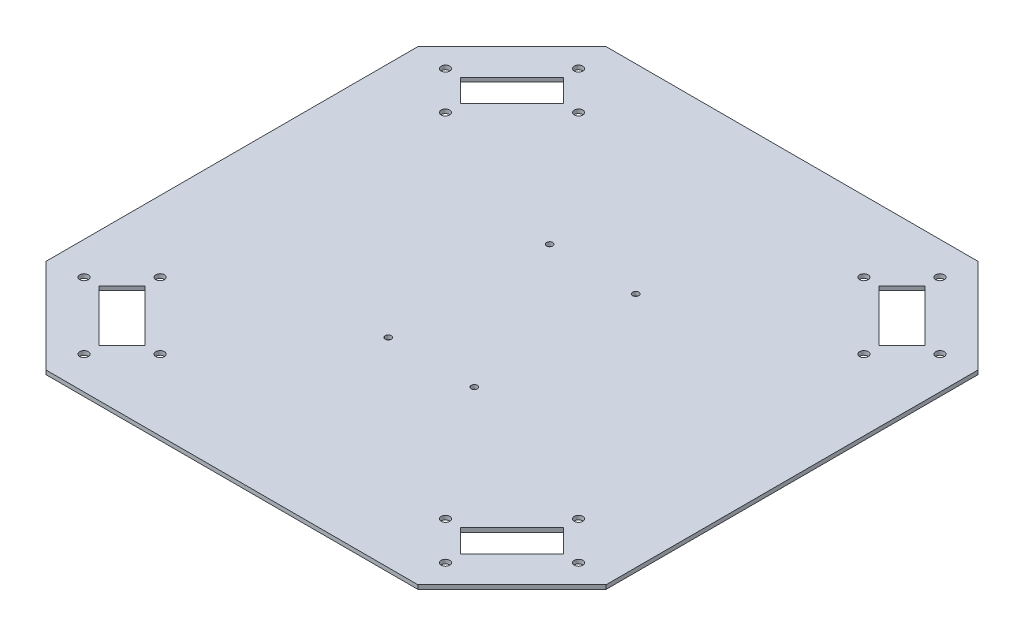
SolidWorks part; units mm, degrees
material "Carbon fiber"
ref_plane "Front Plane" through (0, 0, 0) normal (0, 0, 1) x (1, 0, 0)
ref_plane "Top Plane" through (0, 0, 0) normal (0, 1, 0) x (1, 0, 0)
ref_plane "Right Plane" through (0, 0, 0) normal (1, 0, 0) x (0, 0, -1)
sketch "Sketch2" plane through (0, 0, 0) normal (0, 1, 0) x (1, 0, 0)
  line L0 (91.9419, 67.1932) -> (67.1932, 91.9419) construction
  line L5 (67.1932, 91.9419) -> (53.051, 77.7998) construction
  line L6 (53.051, 77.7998) -> (77.7998, 53.051) construction
  line L7 (77.7998, 53.051) -> (91.9419, 67.1932) construction
  line L8 (-67.1932, 91.9419) -> (-91.9419, 67.1932) construction
  line L9 (-91.9419, 67.1932) -> (-77.7998, 53.051) construction
  line L10 (-77.7998, 53.051) -> (-53.051, 77.7998) construction
  line L11 (-53.051, 77.7998) -> (-67.1932, 91.9419) construction
  line L12 (-67.1932, -91.9419) -> (-91.9419, -67.1932) construction
  line L13 (-91.9419, -67.1932) -> (-77.7998, -53.051) construction
  line L14 (-77.7998, -53.051) -> (-53.051, -77.7998) construction
  line L15 (-53.051, -77.7998) -> (-67.1932, -91.9419) construction
  line L16 (67.1932, -91.9419) -> (91.9419, -67.1932) construction
  line L17 (91.9419, -67.1932) -> (77.7998, -53.051) construction
  line L18 (77.7998, -53.051) -> (53.051, -77.7998) construction
  line L19 (53.051, -77.7998) -> (67.1932, -91.9419) construction
  line L20 (86.6386, 86.6386) -> (79.5675, 79.5675) construction
  line L21 (79.5675, 79.5675) -> (76.7391, 76.7391) construction
  line L22 (-76.7391, -76.7391) -> (-79.5675, -79.5675) construction
  line L23 (-79.5675, -79.5675) -> (-86.6386, -86.6386) construction
  line L24 (-86.6386, 86.6386) -> (-79.5675, 79.5675) construction
  line L25 (-79.5675, 79.5675) -> (-76.7391, 76.7391) construction
  line L26 (104.1386, -69.1386) -> (104.1386, 69.1386)
  line L27 (69.1386, 104.1386) -> (-69.1386, 104.1386)
  line L28 (-104.1386, 69.1386) -> (-104.1386, -69.1386)
  line L29 (-69.1386, -104.1386) -> (69.1386, -104.1386)
  line L30 (86.6386, -86.6386) -> (79.5675, -79.5675) construction
  line L31 (79.5675, -79.5675) -> (76.7391, -76.7391) construction
  line L33 (104.1386, 69.1386) -> (69.1386, 104.1386)
  line L34 (69.1386, -104.1386) -> (104.1386, -69.1386)
  line L35 (-104.1386, -69.1386) -> (-69.1386, -104.1386)
  line L36 (0, 104.1386) -> (0, 0) construction
  line L37 (0, 0) -> (104.1386, 0) construction
  line L38 (86.2851, -67.1932) -> (77.7998, -58.7079)
  line L39 (67.1932, -86.2851) -> (86.2851, -67.1932)
  line L40 (77.7998, -58.7079) -> (58.7079, -77.7998)
  line L41 (58.7079, -77.7998) -> (67.1932, -86.2851)
  line L42 (-67.1932, -86.2851) -> (-58.7079, -77.7998)
  line L43 (-86.2851, -67.1932) -> (-67.1932, -86.2851)
  line L44 (-77.7998, -58.7079) -> (-86.2851, -67.1932)
  line L45 (-58.7079, -77.7998) -> (-77.7998, -58.7079)
  line L46 (-86.2851, 67.1932) -> (-77.7998, 58.7079)
  line L47 (-67.1932, 86.2851) -> (-86.2851, 67.1932)
  line L48 (-58.7079, 77.7998) -> (-67.1932, 86.2851)
  line L49 (-77.7998, 58.7079) -> (-58.7079, 77.7998)
  line L50 (77.7998, 58.7079) -> (86.2851, 67.1932)
  line L51 (86.2851, 67.1932) -> (67.1932, 86.2851)
  line L52 (67.1932, 86.2851) -> (58.7079, 77.7998)
  line L53 (58.7079, 77.7998) -> (77.7998, 58.7079)
  line L54 (-69.1386, 104.1386) -> (-104.1386, 104.1386) construction
  line L55 (-104.1386, 104.1386) -> (-104.1386, 69.1386) construction
  line L56 (-104.1386, -69.1386) -> (-104.1386, -104.1386) construction
  line L57 (-104.1386, -104.1386) -> (-69.1386, -104.1386) construction
  line L58 (69.1386, -104.1386) -> (104.1386, -104.1386) construction
  line L59 (104.1386, -104.1386) -> (104.1386, -69.1386) construction
  line L60 (104.1386, 69.1386) -> (104.1386, 104.1386) construction
  line L61 (104.1386, 104.1386) -> (69.1386, 104.1386) construction
  line L62 (-69.1386, 104.1386) -> (-104.1386, 69.1386)
  line L63 (-16, 0) -> (0, 0) construction
  line L64 (-16, 30) -> (16, 30) construction
  line L65 (-16, 30) -> (-16, -30) construction
  line L66 (-16, -30) -> (16, -30) construction
  line L67 (16, 30) -> (16, -30) construction
  line L68 (0, 0) -> (0, -30) construction
  circle A0 centre (67.1932, -91.9419) radius 1.6
  circle A1 centre (53.051, -77.7998) radius 1.6
  circle A2 centre (77.7998, -53.051) radius 1.6
  circle A3 centre (91.9419, -67.1932) radius 1.6
  circle A4 centre (-67.1932, -91.9419) radius 1.6
  circle A5 centre (-91.9419, -67.1932) radius 1.6
  circle A6 centre (-77.7998, -53.051) radius 1.6
  circle A7 centre (-53.051, -77.7998) radius 1.6
  circle A8 centre (-77.7998, 53.051) radius 1.6
  circle A9 centre (-53.051, 77.7998) radius 1.6
  circle A10 centre (-67.1932, 91.9419) radius 1.6
  circle A11 centre (-91.9419, 67.1932) radius 1.6
  circle A12 centre (77.7998, 53.051) radius 1.6
  circle A13 centre (53.051, 77.7998) radius 1.6
  circle A14 centre (67.1932, 91.9419) radius 1.6
  circle A15 centre (91.9419, 67.1932) radius 1.6
  circle A17 centre (0, 0) radius 125 construction
  circle A18 centre (16, 30) radius 1.15
  circle A19 centre (-16, 30) radius 1.15
  circle A20 centre (-16, -30) radius 1.15
  circle A21 centre (16, -30) radius 1.15
  point P2 (104.1386, -104.1386)
  point P6 (104.1386, 104.1386)
  point P12 (-104.1386, 104.1386)
  point P23 (-104.1386, -104.1386)
  dimension "D1" = 3.2
  dimension "D5" = 3.2
  dimension "D11" = 3.2
  dimension "D16" = 3.2
  dimension "D26" = 250
  dimension "D41" = 2.3
  dimension "D3" = 20
  dimension "D4" = 4
  dimension "D6" = 4
  dimension "D7" = 4
  dimension "D8" = 20
  dimension "D9" = 10
  dimension "D10" = 35
  dimension "D12" = 35
  dimension "D13" = 20
  dimension "D14" = 4
  dimension "D15" = 4
  dimension "D18" = 20
  dimension "D19" = 4
  dimension "D20" = 4
  dimension "D21" = 4
  dimension "D22" = 4
  dimension "D23" = 4
  dimension "D24" = 4
  dimension "D29" = 35
  dimension "D32" = 35
  dimension "D33" = 35
  dimension "D34" = 35
  dimension "D35" = 35
  dimension "D36" = 10
  dimension "D37" = 10
  dimension "D38" = 10
  dimension "D27" = 35
  dimension "D30" = 35
  dimension "D31" = 35
  dimension "D28" = 35
  dimension "D17" = 35
  dimension "D25" = 4
  dimension "D39" = 60
  dimension "D40" = 32
extrude "Boss-Extrude1" add sketch "Sketch2" along normal blind 1.5 contours L27 L62 L28 L35 L29 L34 L26 L33 A21 A20 A19 A18 A15 A14 A13 A12 A11 A10 A9 A8 A7 A6 A5 A4 A3 A2 A1 A0 L41 L40
equation "\"DD_FcMountPatternLengthMm\" = 60"
equation "\"DD_FcMountPatternWidthMm\"= 32"
equation "\"DD_FcHoleMm\"= 2.3"
equation "\"DD_OcMountPatternLengthMm\"= 40"
equation "\"DD_OcMountPatternWidthMm\"= 30"
equation "\"DD_OcHoleMm\"= 3.2"
equation "\"DD_GpsDiamMm\"= 20"
equation "\"DD_GpsLengthMm\"= 20"
equation "\"DD_GpsWidthMm\"= 20"
equation "\"DD_GpsHoleMm\"= 3.2"
equation "\"DD_BattLengthMm\"= 20"
equation "\"DD_BattWidthMm\"= 20"
equation "\"DD_BattHeightMm\"= 20"
equation "\"DD_ArmCount\"= 4"
equation "\"DD_ChassisRadiusMm\"= 250"
equation "\"DD_PlateThicknessMm\"= 1.5"
equation "\"DD_ArmAttachSpacingLongitudinalMm\"= 20"
equation "\"D26@Sketch2\"=\"DD_ChassisRadiusMm\""
equation "\"DD_ArmAttachSpacingOrthogonalMm\" = 35"
equation "\"DD_ArmAttachHoleMm\"= 3.2"
equation "\"D1@Sketch2\"=\"DD_ArmAttachHoleMm\""
equation "\"D3@Sketch2\"=\"DD_ArmAttachSpacingLongitudinalMm\""
equation "\"D27@Sketch2\"=\"DD_ArmAttachSpacingOrthogonalMm\""
equation "\"D36@Sketch2\"=\"DD_ArmAttachSpacingLongitudinalMm\"/2"
equation "\"D4@Sketch2\"=\"DD_ArmAttachSpacingLongitudinalMm\"/5"
equation "\"D23@Sketch2\"=\"D4@Sketch2\""
equation "\"D30@Sketch2\"=\"DD_ArmAttachSpacingOrthogonalMm\""
equation "\"D31@Sketch2\"=\"DD_ArmAttachSpacingOrthogonalMm\""
equation "\"D29@Sketch2\"=\"DD_ArmAttachSpacingOrthogonalMm\""
equation "\"D28@Sketch2\"=\"D29@Sketch2\""
equation "\"D34@Sketch2\"=\"DD_ArmAttachSpacingOrthogonalMm\""
equation "\"D35@Sketch2\"=\"DD_ArmAttachSpacingOrthogonalMm\""
equation "\"D32@Sketch2\"=\"DD_ArmAttachSpacingOrthogonalMm\""
equation "\"D33@Sketch2\"=\"DD_ArmAttachSpacingOrthogonalMm\""
equation "\"D17@Sketch2\"=\"DD_ArmAttachSpacingOrthogonalMm\""
equation "\"D10@Sketch2\"=\"DD_ArmAttachSpacingOrthogonalMm\""
equation "\"D12@Sketch2\"=\"DD_ArmAttachSpacingOrthogonalMm\""
equation "\"D5@Sketch2\"=\"DD_ArmAttachHoleMm\""
equation "\"D11@Sketch2\"=\"DD_ArmAttachHoleMm\""
equation "\"D16@Sketch2\"=\"DD_ArmAttachHoleMm\""
equation "\"D20@Sketch2\"=\"D24@Sketch2\""
equation "\"D24@Sketch2\"=\"DD_ArmAttachSpacingLongitudinalMm\"/5"
equation "\"D38@Sketch2\"=\"DD_ArmAttachSpacingLongitudinalMm\"/2"
equation "\"D18@Sketch2\"=\"DD_ArmAttachSpacingLongitudinalMm\""
equation "\"D19@Sketch2\"=\"D24@Sketch2\""
equation "\"D25@Sketch2\"=\"DD_ArmAttachSpacingLongitudinalMm\"/5"
equation "\"D8@Sketch2\"=\"DD_ArmAttachSpacingLongitudinalMm\""
equation "\"D6@Sketch2\"=\"D25@Sketch2\""
equation "\"D7@Sketch2\"=\"D25@Sketch2\""
equation "\"D9@Sketch2\"=\"DD_ArmAttachSpacingLongitudinalMm\"/2"
equation "\"D37@Sketch2\"=\"DD_ArmAttachSpacingLongitudinalMm\"/2"
equation "\"D15@Sketch2\"=\"DD_ArmAttachSpacingLongitudinalMm\"/5"
equation "\"D13@Sketch2\"=\"DD_ArmAttachSpacingLongitudinalMm\""
equation "\"D14@Sketch2\"=\"D15@Sketch2\""
equation "\"D21@Sketch2\"=\"D15@Sketch2\""
equation "\"D39@Sketch2\"=\"DD_FcMountPatternLengthMm\""
equation "\"D40@Sketch2\"=\"DD_FcMountPatternWidthMm\""
equation "\"D41@Sketch2\"=\"DD_FcHoleMm\""
equation "\"D1@Boss-Extrude1\"=\"DD_PlateThicknessMm\""
